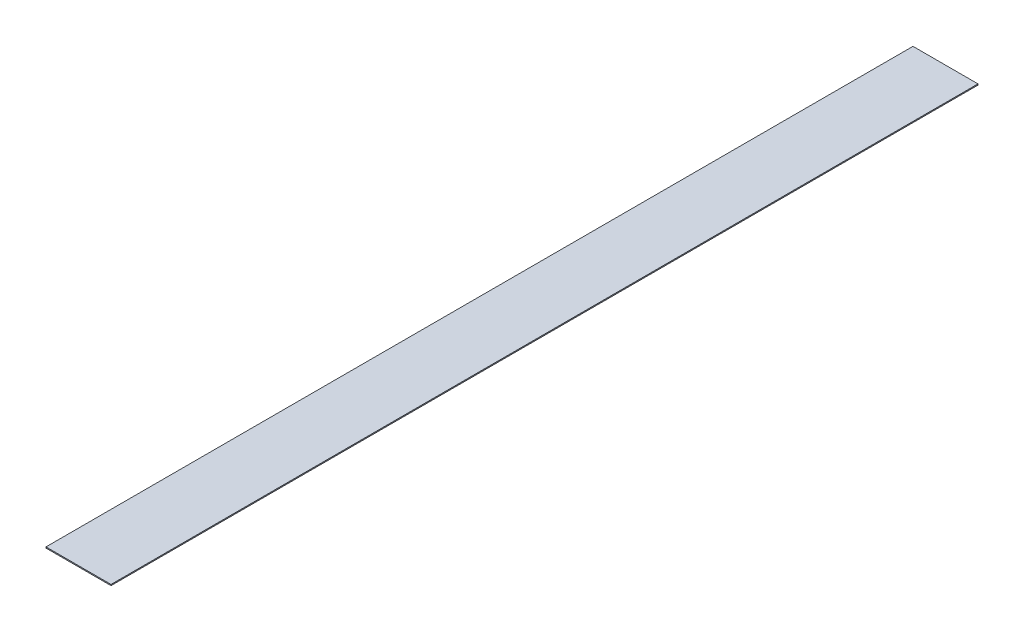
SolidWorks part; units mm, degrees
ref_plane "Front Plane" through (0, 0, 0) normal (0, 0, 1) x (1, 0, 0)
ref_plane "Top Plane" through (0, 0, 0) normal (0, 1, 0) x (1, 0, 0)
ref_plane "Right Plane" through (0, 0, 0) normal (1, 0, 0) x (0, 0, -1)
sketch "Sketch1" plane through (0, 0, 0) normal (0, 1, 0) x (1, 0, 0)
  line L1 (-3000, 40000) -> (3000, 40000)
  line L2 (-3000, 40000) -> (-3000, -40000)
  line L3 (-3000, -40000) -> (3000, -40000)
  line L4 (3000, 40000) -> (3000, -40000)
  point P4 (0, 40000)
  point P6 (3000, 0)
  dimension "D1" = 6000
  dimension "D2" = 80000
extrude "Boss-Extrude1" add sketch "Sketch1" against normal blind 100
